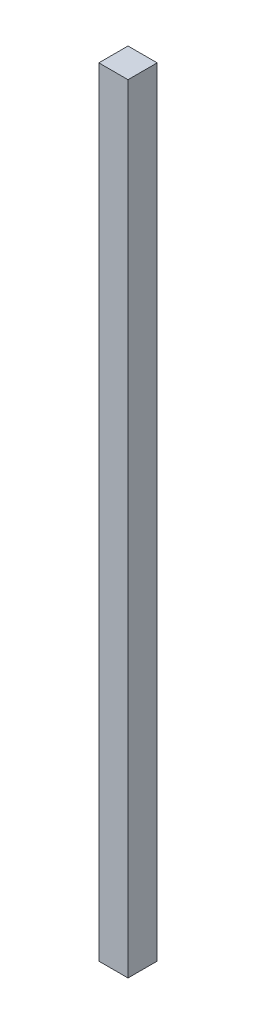
SolidWorks part; units mm, degrees
ref_plane "Front Plane" through (0, 0, 0) normal (0, 0, 1) x (1, 0, 0)
ref_plane "Top Plane" through (0, 0, 0) normal (0, 1, 0) x (1, 0, 0)
ref_plane "Right Plane" through (0, 0, 0) normal (1, 0, 0) x (0, 0, -1)
sketch "Sketch4" plane through (0, 0, 0) normal (0, 1, 0) x (1, 0, 0)
  line L1 (0, 0) -> (15, 0)
  line L2 (0, 0) -> (0, 15)
  line L3 (0, 15) -> (15, 15)
  line L4 (15, 0) -> (15, 15)
  dimension "D1" = 15
extrude "Boss-Extrude2" add sketch "Sketch4" along normal blind 400
